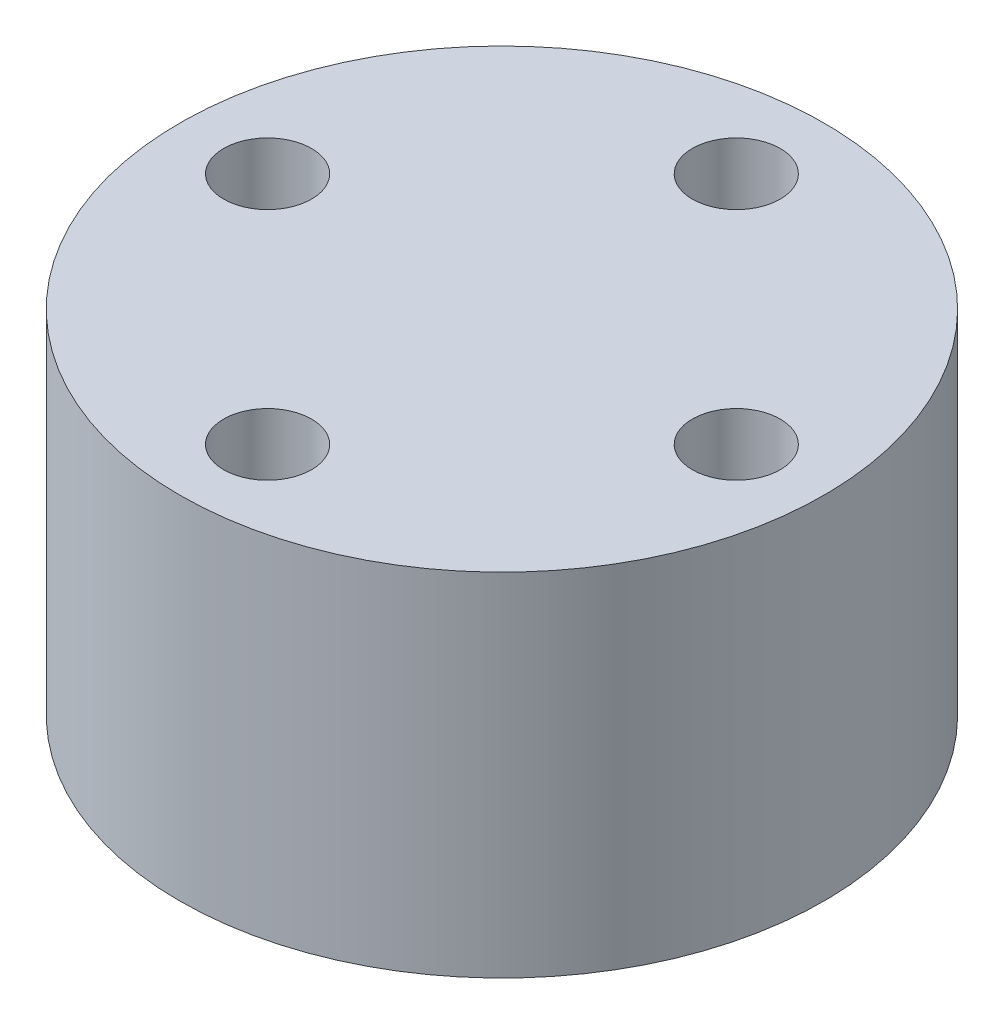
SolidWorks part; units mm, degrees
material "聚脂树脂"
ref_plane "前视基准面" through (0, 0, 0) normal (0, 0, 1) x (1, 0, 0)
ref_plane "上视基准面" through (0, 0, 0) normal (0, 1, 0) x (1, 0, 0)
ref_plane "右视基准面" through (0, 0, 0) normal (1, 0, 0) x (0, 0, -1)
other "Configuration Table"
sketch "草图1" plane through (0, 0, 0) normal (0, 1, 0) x (1, 0, 0)
  line L0 (0, 18.1092) -> (0, -16.3823) construction
  circle A0 centre (0, 0) radius 11
  circle A1 centre (0, 0) radius 8 construction
  circle A2 centre (0, 8) radius 1.5
  circle A3 centre (8, 0) radius 1.5
  circle A4 centre (0, -8) radius 1.5
  circle A5 centre (-8, 0) radius 1.5
  point P17 (0, 0)
  dimension "D1" = 22
  dimension "D2" = 16
  dimension "D3" = 3
  dimension "D4" = 4
extrude "凸台-拉伸1" add sketch "草图1" along normal blind 12
